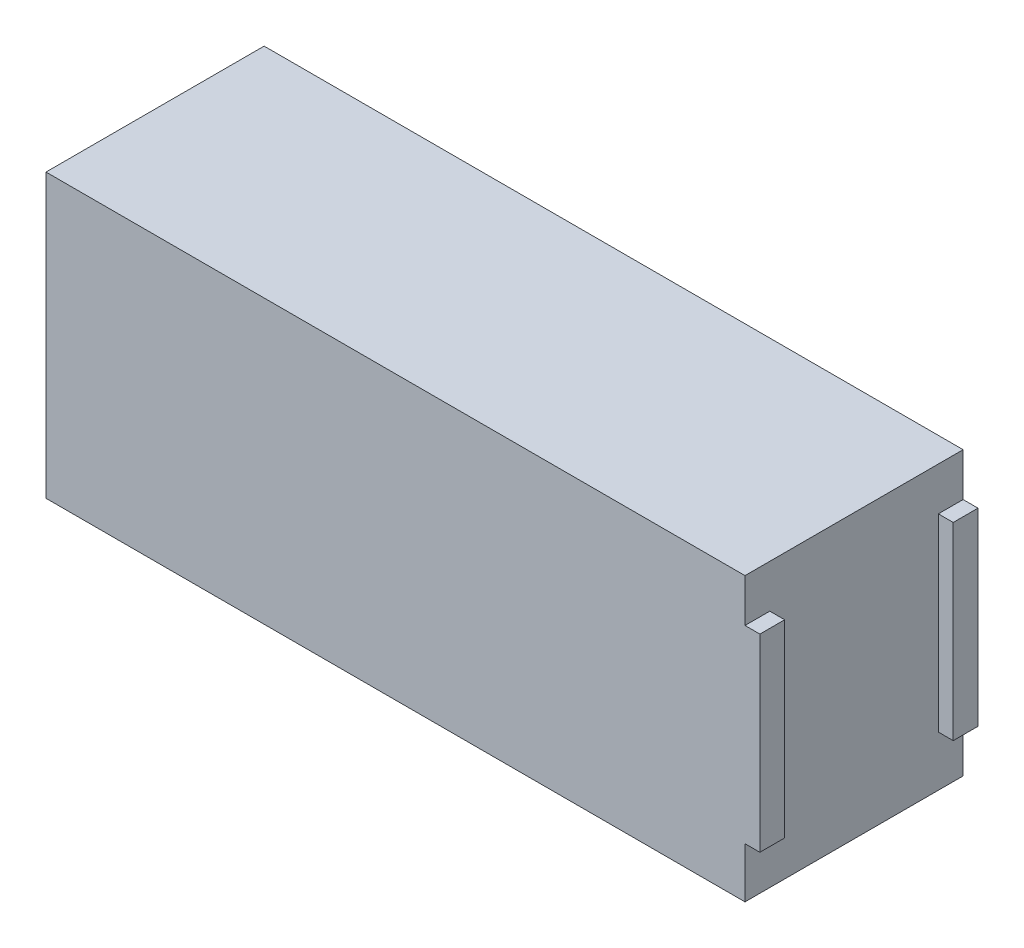
SolidWorks part; units mm, degrees
ref_plane "Спереди" through (0, 0, 0) normal (0, 0, 1) x (1, 0, 0)
ref_plane "Сверху" through (0, 0, 0) normal (0, 1, 0) x (1, 0, 0)
ref_plane "Справа" through (0, 0, 0) normal (1, 0, 0) x (0, 0, -1)
sketch "Эскиз1" plane through (0, 0, 0) normal (0, 1, 0) x (1, 0, 0)
  line L1 (0, 0) -> (141, 0)
  line L2 (0, 0) -> (0, 44)
  line L3 (0, 44) -> (141, 44)
  line L4 (141, 0) -> (141, 44)
  dimension "D1" = 141
  dimension "D2" = 44
extrude "Бобышка-Вытянуть1" add sketch "Эскиз1" along normal blind 57
sketch "Эскиз2" plane through (141, 0, 0) normal (1, 0, 0) x (0, 0, -1)
  line L0 (0, 57) -> (0, 0) construction
  line L1 (0, 48.2874) -> (5, 48.2874)
  line L2 (0, 48.2874) -> (0, 10.1698)
  line L3 (0, 10.1698) -> (5, 10.1698)
  line L4 (5, 48.2874) -> (5, 10.1698)
  line L5 (44, 57) -> (44, 0) construction
  line L6 (44, 10.1698) -> (39, 10.1698)
  line L7 (44, 10.1698) -> (44, 48.2874)
  line L8 (44, 48.2874) -> (39, 48.2874)
  line L9 (39, 10.1698) -> (39, 48.2874)
  dimension "D1" = 5
  dimension "D2" = 5
extrude "Бобышка-Вытянуть2" add sketch "Эскиз2" along normal blind 3
